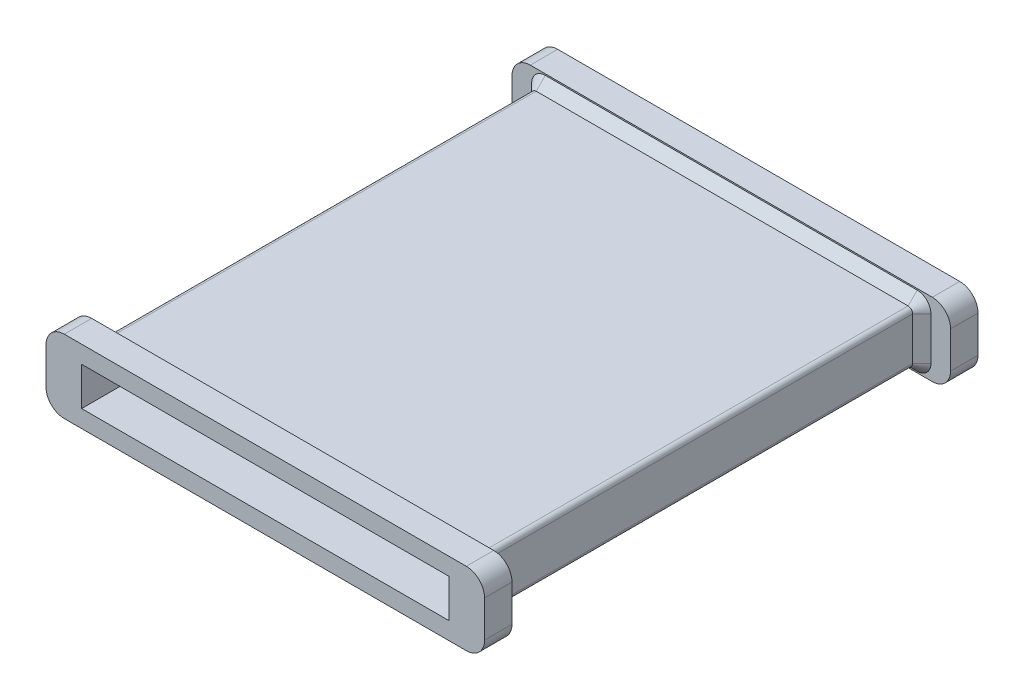
SolidWorks part; units mm, degrees
material "ABS"
ref_plane "Front Plane" through (0, 0, 0) normal (0, 0, 1) x (1, 0, 0)
ref_plane "Top Plane" through (0, 0, 0) normal (0, 1, 0) x (1, 0, 0)
ref_plane "Right Plane" through (0, 0, 0) normal (1, 0, 0) x (0, 0, -1)
sketch "Sketch1" plane through (0, 0, 0) normal (0, 0, 1) x (1, 0, 0)
  line L0 (0, 8) -> (48, 8)
  line L3 (48, 8) -> (48, 0)
  line L4 (48, 0) -> (0, 0)
  line L5 (0, 0) -> (0, 8)
  line L9 (3.9, 6.1) -> (44.1, 6.1)
  line L10 (3.9, 6.1) -> (3.9, 1.9)
  line L11 (3.9, 1.9) -> (44.1, 1.9)
  line L12 (44.1, 6.1) -> (44.1, 1.9)
  dimension "D1" = 1.9
  dimension "D2" = 40.2
  dimension "D4" = 4.2
  dimension "D5" = 1.9
  dimension "D7" = 3.9
  dimension "D8" = 3.9
extrude "Boss-Extrude1" add sketch "Sketch1" along normal blind 54
sketch "Sketch2" plane through (0, 0, 54) normal (0, 0, 1) x (1, 0, 0)
  line L1 (3.65, 6.85) -> (44.35, 6.85)
  line L2 (3.15, 6.35) -> (3.15, 1.65)
  line L3 (3.65, 1.15) -> (44.35, 1.15)
  line L4 (44.85, 6.35) -> (44.85, 1.65)
  line L5 (3.9, 1.9) -> (44.1, 1.9) construction
  line L6 (44.1, 6.1) -> (3.9, 6.1) construction
  line L8 (3.9, 6.1) -> (3.9, 1.9) construction
  line L9 (44.1, 1.9) -> (44.1, 6.1) construction
  arc A0 (3.15, 1.65) -> (3.65, 1.15) centre (3.65, 1.65) ccw
  arc A1 (44.35, 1.15) -> (44.85, 1.65) centre (44.35, 1.65) ccw
  arc A2 (44.35, 6.85) -> (44.85, 6.35) centre (44.35, 6.35) cw
  arc A3 (3.65, 6.85) -> (3.15, 6.35) centre (3.65, 6.35) ccw
  dimension "D1" = 0.5
  dimension "D2" = 0.75
  dimension "D3" = 0.75
  dimension "D4" = 0.75
  dimension "D5" = 0.75
extrude "Cut-Extrude1" cut sketch "Sketch2" against normal offset from surface (48 mm away) 3 from offset 3 flip side to cut up to face at (24, 4, 0) offset against normal yes
fillet "Fillet1" radius 2 8 edges at (48, 8, 52.5) (48, 0, 52.5) (48, 0, 1.5) (48, 8, 1.5) (0, 0, 1.5) (0, 8, 1.5) (0, 0, 52.5) (0, 8, 52.5)
chamfer "Chamfer1" distance 1 angle 45 16 edges at (3.15, 4, 3) (3.2964, 1.2964, 3) (3.2964, 6.7036, 3) (24, 1.15, 3) (24, 6.85, 3) (44.7036, 1.2964, 3) (44.7036, 6.7036, 3) (44.85, 4, 3) (24, 1.15, 51) (44.7036, 1.2964, 51) (3.2964, 1.2964, 51) (44.85, 4, 51) (3.15, 4, 51) (44.7036, 6.7036, 51) (3.2964, 6.7036, 51) (24, 6.85, 51)
